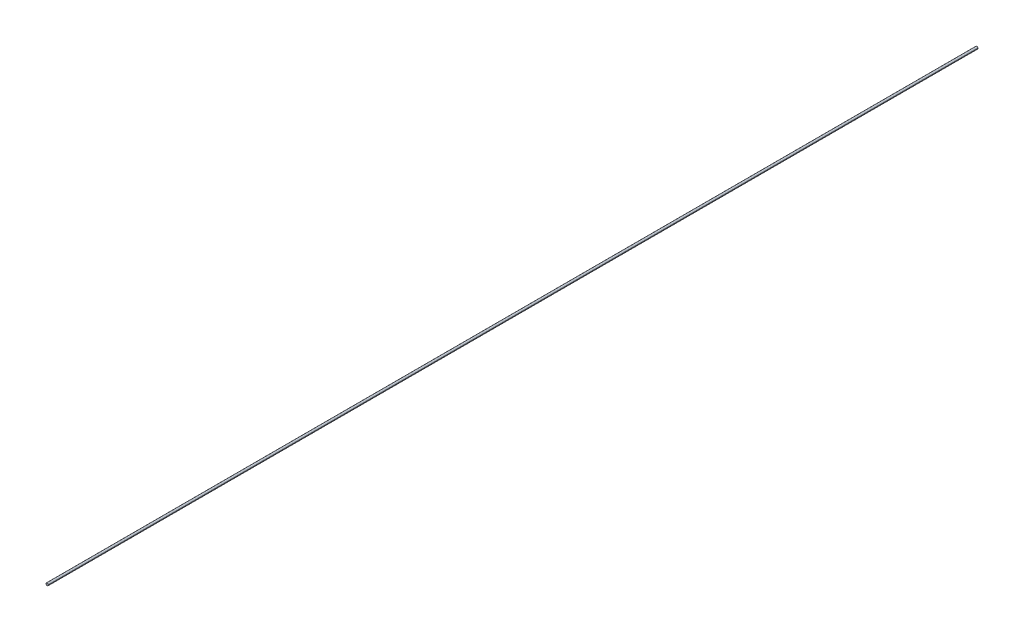
SolidWorks part; units mm, degrees
ref_plane "Alzado" through (0, 0, 0) normal (0, 0, 1) x (1, 0, 0)
ref_plane "Planta" through (0, 0, 0) normal (0, 1, 0) x (1, 0, 0)
ref_plane "Vista lateral" through (0, 0, 0) normal (1, 0, 0) x (0, 0, -1)
sketch "Croquis1" plane through (0, 0, 0) normal (0, 0, 1) x (1, 0, 0)
  circle A0 centre (0, 0) radius 19.05
  dimension "D1" = 38.1
extrude "Saliente-Extruir1" add sketch "Croquis1" along normal blind 15000
sketch "Croquis2" plane through (0, 0, 0) normal (0, 0, -1) x (-1, 0, 0)
  line L1 (-19.3461, -0.2761) -> (-18.7539, -0.2761)
  line L2 (-19.3461, -0.2761) -> (-19.3461, 0.2761)
  line L3 (-19.3461, 0.2761) -> (-18.7539, 0.2761)
  line L4 (-18.7539, -0.2761) -> (-18.7539, 0.2761)
  line L5 (-19.3461, -0.2761) -> (-18.7539, 0.2761) construction
  line L6 (-19.3461, 0.2761) -> (-18.7539, -0.2761) construction
  circle A0 centre (0, 0) radius 19.05 construction
  point P0 (-19.05, 0)
extrude "Saliente-Extruir2" add sketch "Croquis2" against normal up to surface (15000 mm away) up to face at (19.05, 0, 15000)
sketch "Croquis3" plane through (0, 0, 0) normal (0, 0, -1) x (-1, 0, 0)
  line L1 (18.7824, -0.2761) -> (19.3176, -0.2761)
  line L2 (18.7824, -0.2761) -> (18.7824, 0.2761)
  line L3 (18.7824, 0.2761) -> (19.3176, 0.2761)
  line L4 (19.3176, -0.2761) -> (19.3176, 0.2761)
  line L5 (18.7824, -0.2761) -> (19.3176, 0.2761) construction
  line L6 (18.7824, 0.2761) -> (19.3176, -0.2761) construction
  arc A0 (-19.048, -0.2761) -> (-19.048, 0.2761) centre (0, 0) ccw construction
  point P0 (19.05, 0)
extrude "Saliente-Extruir3" add sketch "Croquis3" against normal up to surface (15000 mm away) up to face at (9.6726, 0, 15000)
